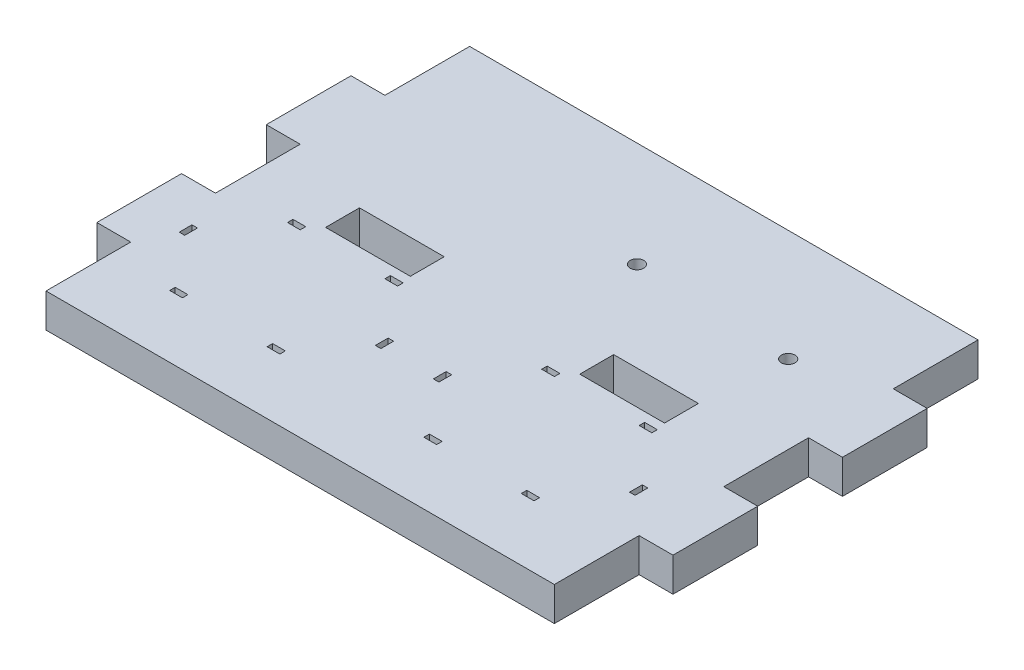
SolidWorks part; units mm, degrees
ref_plane "Front Plane" through (0, 0, 0) normal (0, 0, 1) x (1, 0, 0)
ref_plane "Top Plane" through (0, 0, 0) normal (0, 1, 0) x (1, 0, 0)
ref_plane "Right Plane" through (0, 0, 0) normal (1, 0, 0) x (0, 0, -1)
sketch "Sketch1" plane through (0, 0, 0) normal (0, 1, 0) x (1, 0, 0)
  line L0 (-66.0627, 0) -> (65.2437, 0) construction
  line L1 (-60, 50) -> (60, 50)
  line L2 (-60, 50) -> (-60, -50)
  line L3 (-60, -50) -> (60, -50)
  line L4 (60, 50) -> (60, -50)
  line L5 (27.5, -7.5) -> (27.5, -34) construction
  line L6 (45, 10) -> (-18.5, 10) construction
  line L7 (45, 10) -> (45, 35) construction
  line L8 (45, 35) -> (-18.5, 35) construction
  line L9 (-18.5, 10) -> (-18.5, 35) construction
  line L10 (5, -7.5) -> (50, -7.5) construction
  line L11 (5, -7.5) -> (5, -34) construction
  line L12 (5, -34) -> (50, -34) construction
  line L13 (50, -7.5) -> (50, -34) construction
  line L14 (5, -20.75) -> (50, -20.75) construction
  line L15 (40.5, -7.5) -> (37.5, -7.5)
  line L16 (14.5, -7.5) -> (17.5, -7.5)
  line L17 (14.5, -7.5) -> (14.5, -6.2)
  line L18 (14.5, -6.2) -> (17.5, -6.2)
  line L19 (17.5, -7.5) -> (17.5, -6.2)
  line L20 (5, -19.25) -> (3.7, -19.25)
  line L21 (5, -19.25) -> (5, -22.25)
  line L22 (5, -22.25) -> (3.7, -22.25)
  line L23 (3.7, -19.25) -> (3.7, -22.25)
  line L24 (37.5, -7.5) -> (37.5, -6.2)
  line L25 (40.5, -6.2) -> (37.5, -6.2)
  line L26 (40.5, -7.5) -> (40.5, -6.2)
  line L27 (50, -19.25) -> (51.3, -19.25)
  line L28 (51.3, -19.25) -> (51.3, -22.25)
  line L29 (50, -22.25) -> (51.3, -22.25)
  line L30 (50, -19.25) -> (50, -22.25)
  line L31 (37.5, -34) -> (37.5, -35.3)
  line L32 (40.5, -34) -> (37.5, -34)
  line L33 (40.5, -34) -> (40.5, -35.3)
  line L34 (40.5, -35.3) -> (37.5, -35.3)
  line L35 (14.5, -34) -> (17.5, -34)
  line L36 (17.5, -34) -> (17.5, -35.3)
  line L37 (14.5, -34) -> (14.5, -35.3)
  line L38 (14.5, -35.3) -> (17.5, -35.3)
  line L39 (-2.5, -65.1553) -> (-2.5, 67.8606) construction
  line L46 (-19.5, -35.3) -> (-22.5, -35.3)
  line L47 (-19.5, -34) -> (-19.5, -35.3)
  line L48 (-22.5, -34) -> (-22.5, -35.3)
  line L49 (-19.5, -34) -> (-22.5, -34)
  line L50 (-45.5, -35.3) -> (-42.5, -35.3)
  line L51 (-45.5, -34) -> (-45.5, -35.3)
  line L52 (-45.5, -34) -> (-42.5, -34)
  line L53 (-42.5, -34) -> (-42.5, -35.3)
  line L54 (-55, -19.25) -> (-55, -22.25)
  line L55 (-55, -22.25) -> (-56.3, -22.25)
  line L56 (-56.3, -19.25) -> (-56.3, -22.25)
  line L57 (-55, -19.25) -> (-56.3, -19.25)
  line L58 (-45.5, -7.5) -> (-45.5, -6.2)
  line L59 (-45.5, -6.2) -> (-42.5, -6.2)
  line L60 (-42.5, -7.5) -> (-42.5, -6.2)
  line L61 (-8.7, -19.25) -> (-8.7, -22.25)
  line L62 (-10, -22.25) -> (-8.7, -22.25)
  line L63 (-10, -19.25) -> (-10, -22.25)
  line L64 (-10, -19.25) -> (-8.7, -19.25)
  line L65 (-22.5, -7.5) -> (-22.5, -6.2)
  line L66 (-19.5, -6.2) -> (-22.5, -6.2)
  line L67 (-19.5, -7.5) -> (-19.5, -6.2)
  line L68 (-19.5, -7.5) -> (-22.5, -7.5)
  line L69 (-45.5, -7.5) -> (-42.5, -7.5)
  circle A0 centre (41.5, 23.7) radius 1.6
  circle A1 centre (4.3, 25.2) radius 1.6
  point P4 (60, 0)
  point P6 (0, 50)
  point P33 (5, -20.75)
  dimension "D5" = 3.2
  dimension "D10" = 3.2
  dimension "D17" = 3
  dimension "D18" = 1.3
  dimension "D1" = 120
  dimension "D2" = 100
  dimension "D3" = 10
  dimension "D4" = 15
  dimension "D6" = 3.5
  dimension "D7" = 13.7
  dimension "D8" = 63.5
  dimension "D9" = 25
  dimension "D11" = 40.7
  dimension "D12" = 15.2
  dimension "D13" = 26.5
  dimension "D14" = 45
  dimension "D15" = 7.5
  dimension "D16" = 15
  dimension "D19" = 3
  dimension "D20" = 1.3
  dimension "D21" = 20
  dimension "D22" = 10
extrude "Boss-Extrude1" add sketch "Sketch1" along normal blind 8
sketch "Sketch2" plane through (0, 0, 0) normal (0, -1, 0) x (-1, 0, 0)
  line L1 (-7.4754, 25.2) -> (-5.8877, 22.45)
  line L2 (-5.8877, 22.45) -> (-2.7123, 22.45)
  line L3 (-2.7123, 22.45) -> (-1.1246, 25.2)
  line L4 (-1.1246, 25.2) -> (-2.7123, 27.95)
  line L5 (-2.7123, 27.95) -> (-5.8877, 27.95)
  line L6 (-5.8877, 27.95) -> (-7.4754, 25.2)
  line L7 (-44.6754, 23.7) -> (-43.0877, 20.95)
  line L8 (-43.0877, 20.95) -> (-39.9123, 20.95)
  line L9 (-39.9123, 20.95) -> (-38.3246, 23.7)
  line L10 (-38.3246, 23.7) -> (-39.9123, 26.45)
  line L11 (-39.9123, 26.45) -> (-43.0877, 26.45)
  line L12 (-43.0877, 26.45) -> (-44.6754, 23.7)
  circle A0 centre (-4.3, 25.2) radius 2.75 construction
  circle A1 centre (-41.5, 23.7) radius 2.75 construction
  dimension "D1" = 5.5
  dimension "D2" = 5.5
extrude "Cut-Extrude1" cut sketch "Sketch2" against normal blind 4
sketch "Sketch3" plane through (-60, 0, 0) normal (-1, 0, 0) x (0, 0, 1)
  line L0 (-50, 8) -> (-50, 0) construction
  line L1 (-30, 0) -> (-10, 0)
  line L2 (-30, 0) -> (-30, 8)
  line L3 (-30, 8) -> (-10, 8)
  line L4 (-10, 0) -> (-10, 8)
  line L5 (-50, 0) -> (50, 0) construction
  line L6 (0, 15.2289) -> (0, -7.9114) construction
  line L7 (10, 0) -> (10, 8)
  line L8 (30, 8) -> (10, 8)
  line L9 (30, 0) -> (30, 8)
  line L10 (30, 0) -> (10, 0)
  dimension "D1" = 20
  dimension "D2" = 20
extrude "Boss-Extrude2" add sketch "Sketch3" along normal blind 8
ref_plane "Plane1" through (0, 0, 0) normal (-1, 0, 0) x (0, 0, 1)
mirror "Mirror1" about plane through (0, 0, 0) normal (-1, 0, 0) of "Boss-Extrude2"
sketch "Sketch5" plane through (0, 0, 0) normal (0, -1, 0) x (-1, 0, 0)
  line L0 (74.0532, 0) -> (-79.4319, 0) construction
  line L1 (20, 4) -> (40, 4)
  line L2 (20, 4) -> (20, -4)
  line L3 (20, -4) -> (40, -4)
  line L4 (40, 4) -> (40, -4)
  line L5 (0, -4.4) -> (0, 4.4) construction
  point P7 (20, 0)
  dimension "D1" = 20
  dimension "D2" = 8
  dimension "D3" = 20
extrude "Cut-Extrude3" cut sketch "Sketch5" against normal up to next
mirror "Mirror2" about plane through (0, 0, 0) normal (-1, 0, 0) of "Cut-Extrude3"
